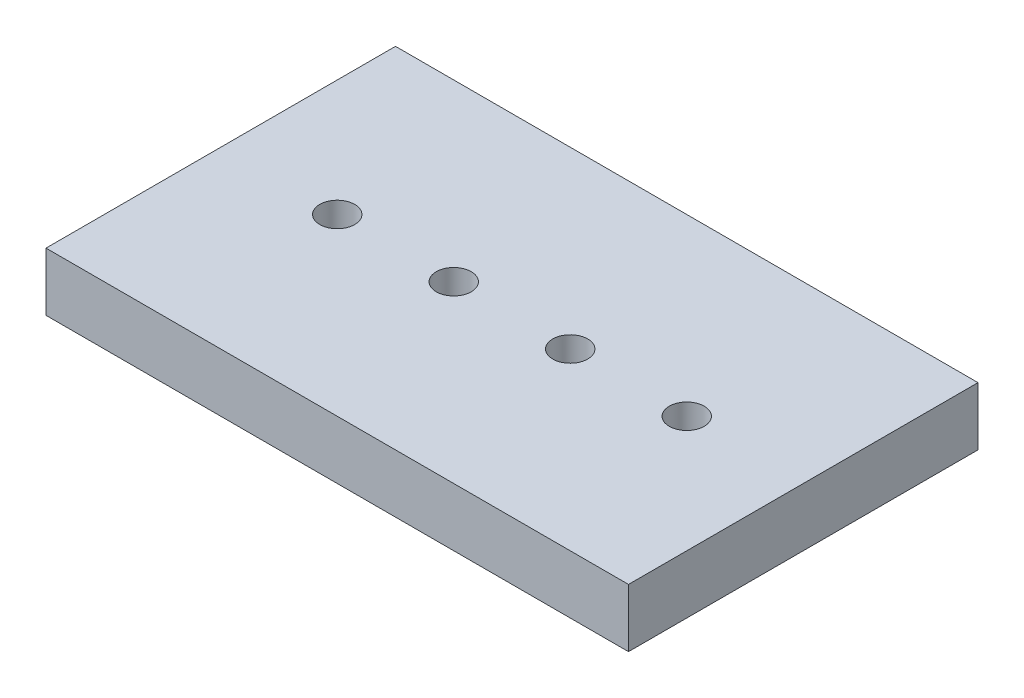
SolidWorks part; units mm, degrees
ref_plane "前视基准面" through (0, 0, 0) normal (0, 0, 1) x (1, 0, 0)
ref_plane "上视基准面" through (0, 0, 0) normal (0, 1, 0) x (1, 0, 0)
ref_plane "右视基准面" through (0, 0, 0) normal (1, 0, 0) x (0, 0, -1)
other "Configuration Table"
sketch "草图1" plane through (0, 0, 0) normal (0, 1, 0) x (1, 0, 0)
  line L1 (-50, -30) -> (50, -30)
  line L2 (-50, -30) -> (-50, 30)
  line L3 (-50, 30) -> (50, 30)
  line L4 (50, -30) -> (50, 30)
  line L5 (-50, -30) -> (50, 30) construction
  line L6 (-50, 30) -> (50, -30) construction
  point P0 (0, 0)
extrude "凸台-拉伸1" add sketch "草图1" along normal blind 10
sketch "草图2" plane through (0, 0, 0) normal (0, 1, 0) x (1, 0, 0)
  circle A0 centre (-30, 0) radius 3
extrude "切除-拉伸1" cut sketch "草图2" along normal blind 20
pattern_linear "阵列(线性)1" count 4 spacing 20 along (1, 0, 0) of "切除-拉伸1"
